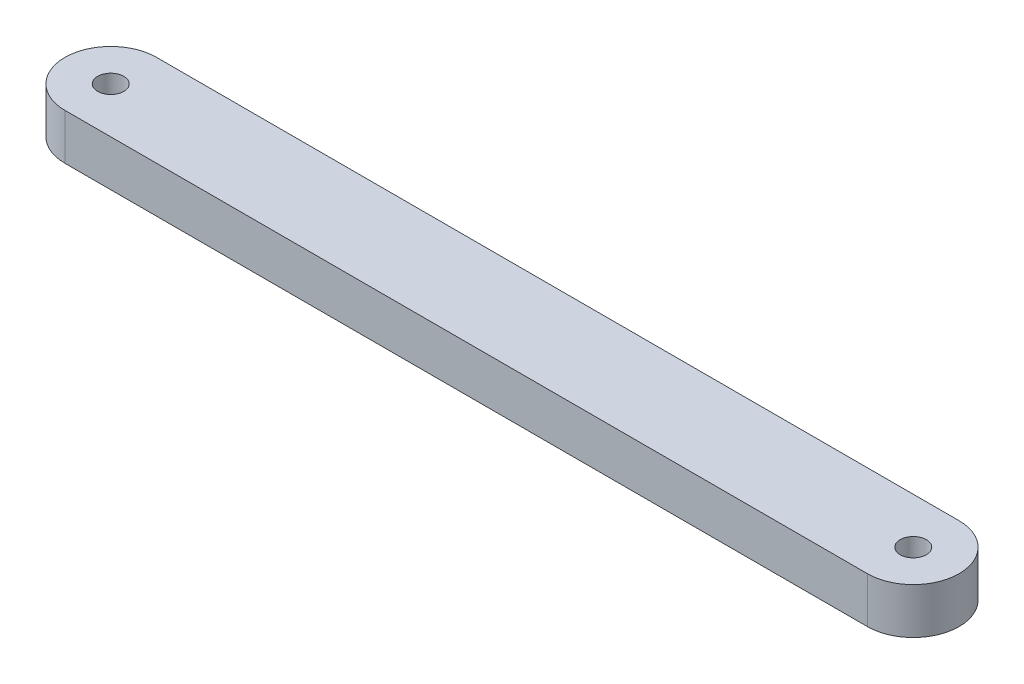
SolidWorks part; units mm, degrees
ref_plane "Front Plane" through (0, 0, 0) normal (0, 0, 1) x (1, 0, 0)
ref_plane "Top Plane" through (0, 0, 0) normal (0, 1, 0) x (1, 0, 0)
ref_plane "Right Plane" through (0, 0, 0) normal (1, 0, 0) x (0, 0, -1)
sketch "Sketch1" plane through (0, 0, 0) normal (0, 1, 0) x (1, 0, 0)
  line L0 (-44.45, 5.08) -> (44.45, 5.08)
  line L1 (-44.45, -5.08) -> (44.45, -5.08)
  circle A0 centre (-44.45, 0) radius 1.45
  circle A1 centre (44.45, 0) radius 1.45
  arc A2 (-44.45, 5.08) -> (-44.45, -5.08) centre (-44.45, 0) ccw
  arc A3 (44.45, 5.08) -> (44.45, -5.08) centre (44.45, 0) cw
  dimension "D3" = 2.9
  dimension "D4" = 2.9
  dimension "D5" = 5.08
  dimension "D1" = 88.9
  dimension "D2" = 44.45
extrude "Boss-Extrude1" add sketch "Sketch1" along normal blind 5.08
